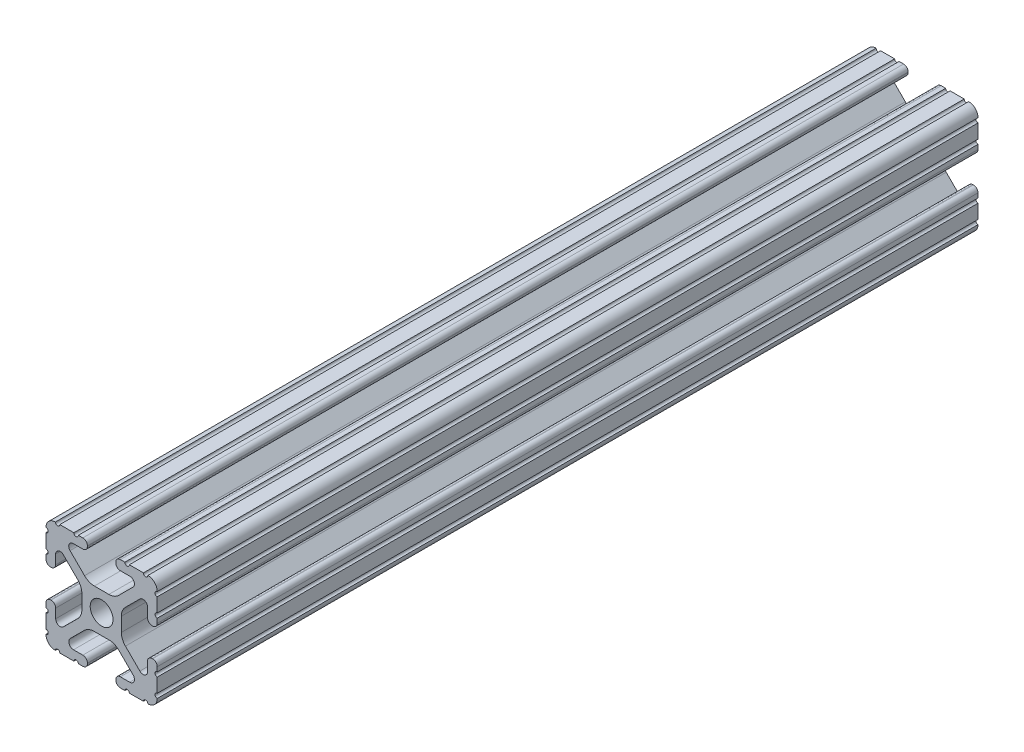
SolidWorks part; units mm, degrees
ref_plane "Front Plane" through (0, 0, 0) normal (0, 0, 1) x (1, 0, 0)
ref_plane "Top Plane" through (0, 0, 0) normal (0, 1, 0) x (1, 0, 0)
ref_plane "Right Plane" through (0, 0, 0) normal (1, 0, 0) x (0, 0, -1)
sketch "Sketch1" plane through (0, 0, 0) normal (0, 0, 1) x (1, 0, 0)
  line L88 (-7.1797, -8.6452) -> (-3.9523, -5.4237)
  line L89 (-1.7093, -4.4958) -> (1.7093, -4.4958)
  line L90 (3.9523, -5.4237) -> (7.1797, -8.6452)
  line L91 (6.4164, -10.4902) -> (4.2875, -10.4902)
  line L92 (3.2385, -11.5392) -> (3.2385, -11.651)
  line L93 (4.2875, -12.7) -> (5.3171, -12.7)
  line L94 (6.3331, -12.7) -> (9.5504, -12.7)
  line L95 (12.7, -9.5504) -> (12.7, -6.3331)
  line L96 (12.7, -5.3171) -> (12.7, -4.2875)
  line L97 (11.651, -3.2385) -> (11.5392, -3.2385)
  line L98 (10.4902, -4.2875) -> (10.4902, -6.4021)
  line L99 (8.7371, -7.1294) -> (5.441, -3.8408)
  line L100 (4.5085, -1.5932) -> (4.5085, 1.5932)
  line L101 (5.441, 3.8408) -> (8.7371, 7.1294)
  line L102 (10.4902, 6.4021) -> (10.4902, 4.2875)
  line L103 (11.5392, 3.2385) -> (11.651, 3.2385)
  line L104 (12.7, 4.2875) -> (12.7, 5.3171)
  line L105 (12.7, 6.3331) -> (12.7, 9.5504)
  line L106 (9.5504, 12.7) -> (6.3331, 12.7)
  line L107 (5.3171, 12.7) -> (4.2875, 12.7)
  line L108 (3.2385, 11.651) -> (3.2385, 11.5392)
  line L109 (4.2875, 10.4902) -> (6.4768, 10.4902)
  line L110 (7.207, 8.7244) -> (3.8983, 5.4232)
  line L111 (1.6558, 4.4958) -> (-1.6558, 4.4958)
  line L112 (-3.8983, 5.4232) -> (-7.207, 8.7244)
  line L113 (-6.4768, 10.4902) -> (-4.2875, 10.4902)
  line L114 (-3.2385, 11.5392) -> (-3.2385, 11.651)
  line L115 (-4.2875, 12.7) -> (-5.3171, 12.7)
  line L116 (-6.3331, 12.7) -> (-9.5504, 12.7)
  line L117 (-12.7, 9.5504) -> (-12.7, 6.3331)
  line L118 (-12.7, 5.3171) -> (-12.7, 4.2875)
  line L119 (-11.651, 3.2385) -> (-11.5392, 3.2385)
  line L120 (-10.4902, 4.2875) -> (-10.4902, 6.4021)
  line L121 (-8.7371, 7.1294) -> (-5.441, 3.8408)
  line L122 (-4.5085, 1.5932) -> (-4.5085, -1.5932)
  line L123 (-5.441, -3.8408) -> (-8.7371, -7.1294)
  line L124 (-10.4902, -6.4021) -> (-10.4902, -4.2875)
  line L125 (-11.5392, -3.2385) -> (-11.651, -3.2385)
  line L126 (-12.7, -4.2875) -> (-12.7, -5.3171)
  line L127 (-12.7, -6.3331) -> (-12.7, -9.5504)
  line L128 (-9.5504, -12.7) -> (-6.3331, -12.7)
  line L129 (-5.3171, -12.7) -> (-4.2875, -12.7)
  line L130 (-3.2385, -11.651) -> (-3.2385, -11.5392)
  line L131 (-4.2875, -10.4902) -> (-6.4164, -10.4902)
  circle A1 centre (0, 0) radius 2.6035
  arc A104 (-7.1797, -8.6452) -> (-6.4164, -10.4902) centre (-6.4164, -9.4098) ccw
  arc A105 (-1.7093, -4.4958) -> (-3.9523, -5.4237) centre (-1.7093, -7.6708) ccw
  arc A106 (3.9523, -5.4237) -> (1.7093, -4.4958) centre (1.7093, -7.6708) ccw
  arc A107 (6.4164, -10.4902) -> (7.1797, -8.6452) centre (6.4164, -9.4098) ccw
  arc A108 (4.2875, -10.4902) -> (3.2385, -11.5392) centre (4.2875, -11.5392) ccw
  arc A109 (3.2385, -11.651) -> (4.2875, -12.7) centre (4.2875, -11.651) ccw
  arc A110 (6.3331, -12.7) -> (5.3171, -12.7) centre (5.8251, -12.7) ccw
  arc A111 (10.5664, -12.6998) -> (9.5504, -12.7) centre (10.0584, -12.7) ccw
  arc A112 (10.5664, -12.6998) -> (12.6998, -10.5664) centre (10.5918, -10.5918) ccw
  arc A113 (12.7, -9.5504) -> (12.6998, -10.5664) centre (12.7, -10.0584) ccw
  arc A114 (12.7, -5.3171) -> (12.7, -6.3331) centre (12.7, -5.8251) ccw
  arc A115 (12.7, -4.2875) -> (11.651, -3.2385) centre (11.651, -4.2875) ccw
  arc A116 (11.5392, -3.2385) -> (10.4902, -4.2875) centre (11.5392, -4.2875) ccw
  arc A117 (8.7371, -7.1294) -> (10.4902, -6.4021) centre (9.4628, -6.4021) ccw
  arc A118 (4.5085, -1.5932) -> (5.441, -3.8408) centre (7.6835, -1.5932) ccw
  arc A119 (5.441, 3.8408) -> (4.5085, 1.5932) centre (7.6835, 1.5932) ccw
  arc A120 (10.4902, 6.4021) -> (8.7371, 7.1294) centre (9.4628, 6.4021) ccw
  arc A121 (10.4902, 4.2875) -> (11.5392, 3.2385) centre (11.5392, 4.2875) ccw
  arc A122 (11.651, 3.2385) -> (12.7, 4.2875) centre (11.651, 4.2875) ccw
  arc A123 (12.7, 6.3331) -> (12.7, 5.3171) centre (12.7, 5.8251) ccw
  arc A124 (12.6998, 10.5664) -> (12.7, 9.5504) centre (12.7, 10.0584) ccw
  arc A125 (12.6998, 10.5664) -> (10.5664, 12.6998) centre (10.5918, 10.5918) ccw
  arc A126 (9.5504, 12.7) -> (10.5664, 12.6998) centre (10.0584, 12.7) ccw
  arc A127 (5.3171, 12.7) -> (6.3331, 12.7) centre (5.8251, 12.7) ccw
  arc A128 (4.2875, 12.7) -> (3.2385, 11.651) centre (4.2875, 11.651) ccw
  arc A129 (3.2385, 11.5392) -> (4.2875, 10.4902) centre (4.2875, 11.5392) ccw
  arc A130 (7.207, 8.7244) -> (6.4768, 10.4902) centre (6.4768, 9.4563) ccw
  arc A131 (1.6558, 4.4958) -> (3.8983, 5.4232) centre (1.6558, 7.6708) ccw
  arc A132 (-3.8983, 5.4232) -> (-1.6558, 4.4958) centre (-1.6558, 7.6708) ccw
  arc A133 (-6.4768, 10.4902) -> (-7.207, 8.7244) centre (-6.4768, 9.4563) ccw
  arc A134 (-4.2875, 10.4902) -> (-3.2385, 11.5392) centre (-4.2875, 11.5392) ccw
  arc A135 (-3.2385, 11.651) -> (-4.2875, 12.7) centre (-4.2875, 11.651) ccw
  arc A136 (-6.3331, 12.7) -> (-5.3171, 12.7) centre (-5.8251, 12.7) ccw
  arc A137 (-10.5664, 12.6998) -> (-9.5504, 12.7) centre (-10.0584, 12.7) ccw
  arc A138 (-10.5664, 12.6998) -> (-12.6998, 10.5664) centre (-10.5918, 10.5918) ccw
  arc A139 (-12.7, 9.5504) -> (-12.6998, 10.5664) centre (-12.7, 10.0584) ccw
  arc A140 (-12.7, 5.3171) -> (-12.7, 6.3331) centre (-12.7, 5.8251) ccw
  arc A141 (-12.7, 4.2875) -> (-11.651, 3.2385) centre (-11.651, 4.2875) ccw
  arc A142 (-11.5392, 3.2385) -> (-10.4902, 4.2875) centre (-11.5392, 4.2875) ccw
  arc A143 (-8.7371, 7.1294) -> (-10.4902, 6.4021) centre (-9.4628, 6.4021) ccw
  arc A144 (-4.5085, 1.5932) -> (-5.441, 3.8408) centre (-7.6835, 1.5932) ccw
  arc A145 (-5.441, -3.8408) -> (-4.5085, -1.5932) centre (-7.6835, -1.5932) ccw
  arc A146 (-10.4902, -6.4021) -> (-8.7371, -7.1294) centre (-9.4628, -6.4021) ccw
  arc A147 (-10.4902, -4.2875) -> (-11.5392, -3.2385) centre (-11.5392, -4.2875) ccw
  arc A148 (-11.651, -3.2385) -> (-12.7, -4.2875) centre (-11.651, -4.2875) ccw
  arc A149 (-12.7, -6.3331) -> (-12.7, -5.3171) centre (-12.7, -5.8251) ccw
  arc A150 (-12.6998, -10.5664) -> (-12.7, -9.5504) centre (-12.7, -10.0584) ccw
  arc A151 (-12.6998, -10.5664) -> (-10.5664, -12.6998) centre (-10.5918, -10.5918) ccw
  arc A152 (-9.5504, -12.7) -> (-10.5664, -12.6998) centre (-10.0584, -12.7) ccw
  arc A153 (-5.3171, -12.7) -> (-6.3331, -12.7) centre (-5.8251, -12.7) ccw
  arc A154 (-4.2875, -12.7) -> (-3.2385, -11.651) centre (-4.2875, -11.651) ccw
  arc A155 (-3.2385, -11.5392) -> (-4.2875, -10.4902) centre (-4.2875, -11.5392) ccw
extrude "Boss-Extrude1" add sketch "Sketch1" along normal mid plane 187.452
